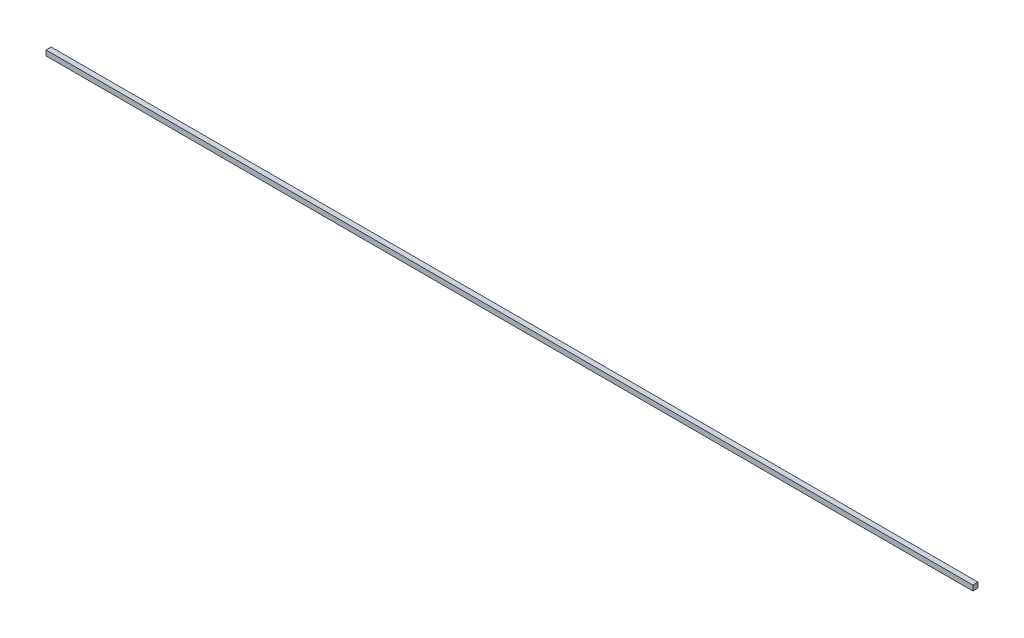
SolidWorks part; units mm, degrees
material "Balsa"
ref_plane "Front Plane" through (0, 0, 0) normal (0, 0, 1) x (1, 0, 0)
ref_plane "Top Plane" through (0, 0, 0) normal (0, 1, 0) x (1, 0, 0)
ref_plane "Right Plane" through (0, 0, 0) normal (1, 0, 0) x (0, 0, -1)
sketch "Sketch1" plane through (0, 0, 0) normal (1, 0, 0) x (0, 0, -1)
  line L1 (2.5, 2.5) -> (-2.5, 2.5)
  line L2 (2.5, 2.5) -> (2.5, -2.5)
  line L3 (2.5, -2.5) -> (-2.5, -2.5)
  line L4 (-2.5, 2.5) -> (-2.5, -2.5)
  line L5 (2.5, 2.5) -> (-2.5, -2.5) construction
  line L6 (2.5, -2.5) -> (-2.5, 2.5) construction
  point P0 (0, 0)
  dimension "D1" = 5
  dimension "D2" = 5
extrude "Boss-Extrude1" add sketch "Sketch1" along normal blind 900
